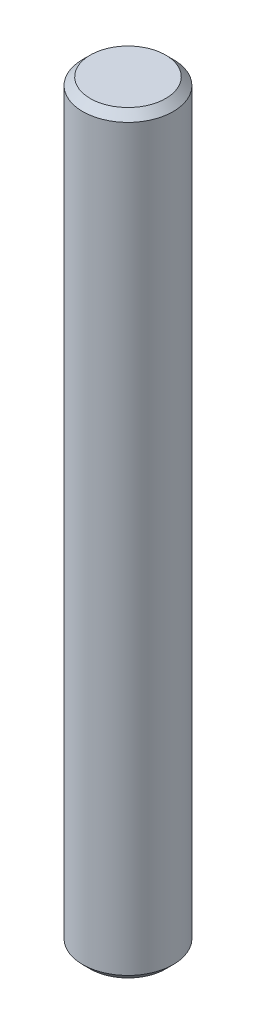
SolidWorks part; units mm, degrees
ref_plane "Front Plane" through (0, 0, 0) normal (0, 0, 1) x (1, 0, 0)
ref_plane "Top Plane" through (0, 0, 0) normal (0, 1, 0) x (1, 0, 0)
ref_plane "Right Plane" through (0, 0, 0) normal (1, 0, 0) x (0, 0, -1)
sketch "Sketch1" plane through (0, 0, 0) normal (0, 1, 0) x (1, 0, 0)
  circle A0 centre (0, 0) radius 1.5
extrude "Boss-Extrude1" add sketch "Sketch1" along normal mid plane 25
chamfer "Chamfer1" distance 0.25 angle 45 2 edges at (0, -12.5, 1.5) (0, 12.5, 1.5)
